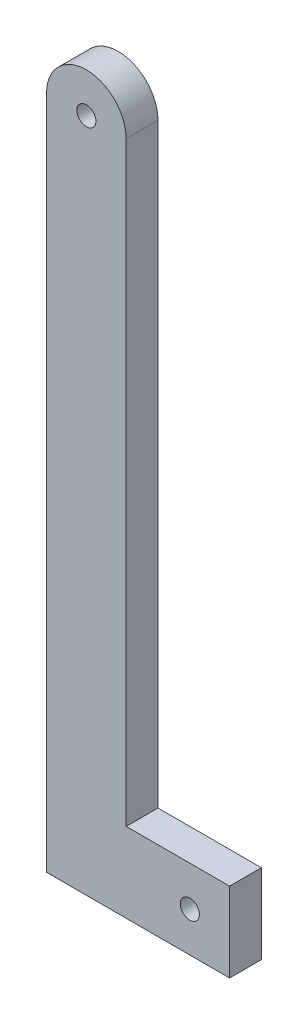
SolidWorks part; units mm, degrees
ref_plane "Front Plane" through (0, 0, 0) normal (0, 0, 1) x (1, 0, 0)
ref_plane "Top Plane" through (0, 0, 0) normal (0, 1, 0) x (1, 0, 0)
ref_plane "Right Plane" through (0, 0, 0) normal (1, 0, 0) x (0, 0, -1)
sketch "Sketch1" plane through (0, 0, 0) normal (0, 0, 1) x (1, 0, 0)
  line L0 (-12.5, 0) -> (-12.5, -212.109)
  line L1 (12.5, 0) -> (12.5, -187.109)
  line L2 (-12.5, -93.5545) -> (12.5, -93.5545) construction
  line L3 (12.5, -199.609) -> (32.5, -199.609) construction
  line L4 (-12.5, -212.109) -> (45, -212.109)
  line L5 (45, -212.109) -> (45, -187.109)
  line L6 (45, -187.109) -> (12.5, -187.109)
  line L7 (45, -199.609) -> (20, -199.609) construction
  circle A0 centre (0, 0) radius 3
  arc A1 (12.5, 0) -> (-12.5, 0) centre (0, 0) ccw
  circle A4 centre (32.5, -199.609) radius 3
  point P13 (32.5, -199.609)
  dimension "D1" = 6
  dimension "D2" = 25
  dimension "D4" = 20
  dimension "D3" = 200
extrude "Boss-Extrude1" add sketch "Sketch1" along normal blind 10
